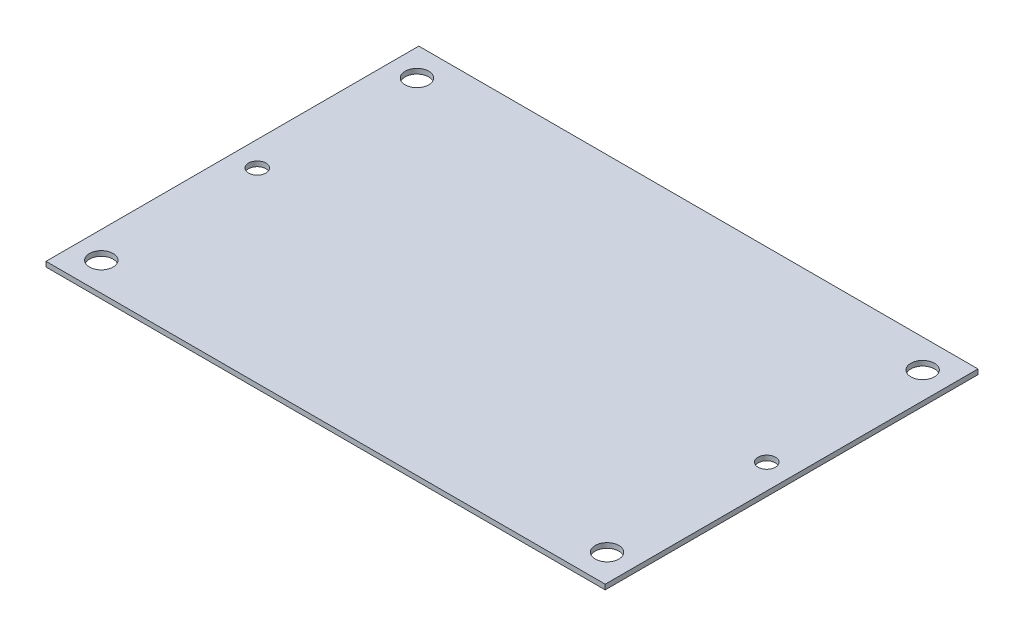
SolidWorks part; units mm, degrees
ref_plane "Спереди" through (0, 0, 0) normal (0, 0, 1) x (1, 0, 0)
ref_plane "Сверху" through (0, 0, 0) normal (0, 1, 0) x (1, 0, 0)
ref_plane "Справа" through (0, 0, 0) normal (1, 0, 0) x (0, 0, -1)
sketch "Эскиз1" plane through (0, 0, 0) normal (0, 1, 0) x (1, 0, 0)
  line L1 (0, 0) -> (450, 0)
  line L2 (0, 0) -> (0, 300)
  line L3 (0, 300) -> (450, 300)
  line L4 (450, 0) -> (450, 300)
  dimension "D1" = 450
  dimension "D2" = 300
extrude "Бобышка-Вытянуть1" add sketch "Эскиз1" along normal blind 4
sketch "Эскиз2" plane through (0, 4, 0) normal (0, 1, 0) x (1, 0, 0)
  circle A0 centre (11.5661, 12.4374) radius 2.25 construction
  circle A1 centre (11.5661, 12.4374) radius 2.25
  circle A2 centre (10.9374, 32.9339) radius 2.25 construction
  circle A3 centre (10.9374, 32.9339) radius 2.25
  circle A4 centre (21.5, 23) radius 9.5 construction
  circle A5 centre (21.5, 23) radius 9.5
  circle A6 centre (12.3658, 147.6087) radius 2 construction
  circle A7 centre (12.3658, 147.6087) radius 2
  circle A8 centre (27.6342, 152.3913) radius 2 construction
  circle A9 centre (27.6342, 152.3913) radius 2
  circle A10 centre (20, 150) radius 7 construction
  circle A11 centre (20, 150) radius 7
  circle A12 centre (21.5, 277) radius 9.5 construction
  circle A13 centre (21.5, 277) radius 9.5
  circle A14 centre (428.5, 23) radius 9.5 construction
  circle A15 centre (428.5, 23) radius 9.5
  circle A16 centre (430, 150) radius 7 construction
  circle A17 centre (430, 150) radius 7
  circle A18 centre (428.5, 277) radius 9.5 construction
  circle A19 centre (428.5, 277) radius 9.5
extrude "Вырез-Вытянуть1" cut sketch "Эскиз2" against normal blind 10 contours A11 | A5 | A15 | A17 | A19 | A13
sketch "Эскиз3" plane through (0, 4, 0) normal (0, 1, 0) x (1, 0, 0)
  line L0 (0, 0) -> (450, 0) construction
  line L1 (370.5266, 278.6158) -> (102.1161, 278.6158) construction
  line L2 (370.5266, 278.6158) -> (370.5266, 3.0855) construction
  line L3 (370.5266, 3.0855) -> (102.1161, 3.0855) construction
  line L4 (102.1161, 278.6158) -> (102.1161, 3.0855) construction
  line L5 (0, 300) -> (0, 0) construction
  line L10 (450, 0) -> (450, 300) construction
  line L11 (450, 300) -> (0, 300) construction
  dimension "D1" = 3.0855
  dimension "D2" = 102.1161
  dimension "D3" = 79.4734
  dimension "D4" = 21.3842
  dimension "D5" = 268.4104
  dimension "D6" = 275.5303
